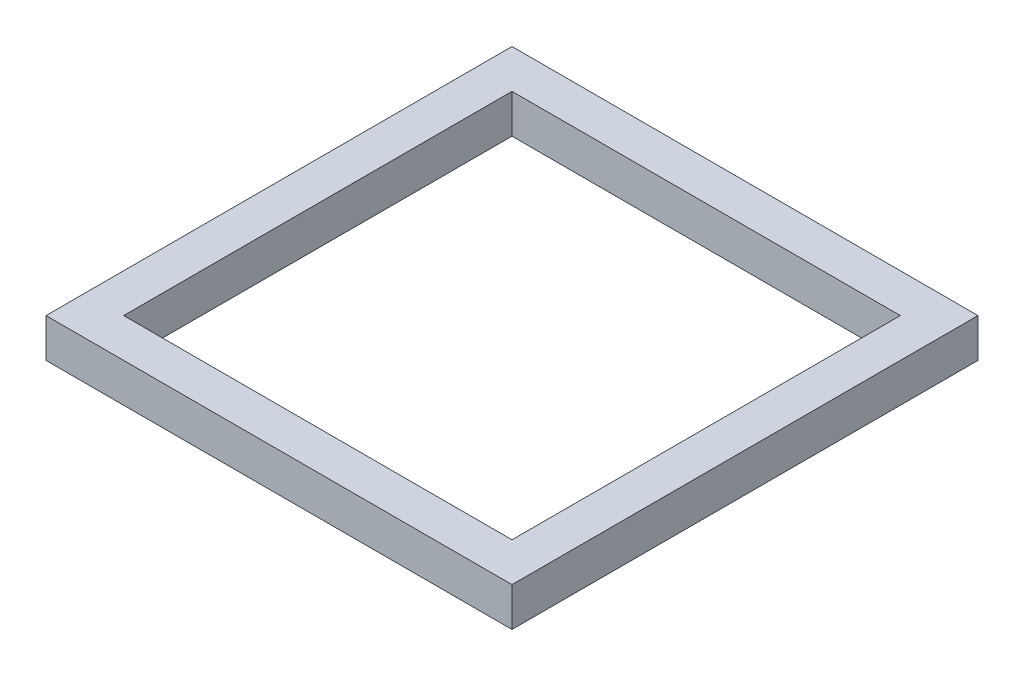
SolidWorks part; units mm, degrees
ref_plane "Front Plane" through (0, 0, 0) normal (0, 0, 1) x (1, 0, 0)
ref_plane "Top Plane" through (0, 0, 0) normal (0, 1, 0) x (1, 0, 0)
ref_plane "Right Plane" through (0, 0, 0) normal (1, 0, 0) x (0, 0, -1)
sketch "Sketch3" plane through (0, 0, 0) normal (0, 1, 0) x (1, 0, 0)
  line L0 (-25, 25) -> (25, 25)
  line L1 (-30, -30) -> (30, -30)
  line L2 (-30, -30) -> (-30, 30)
  line L3 (-30, 30) -> (30, 30)
  line L4 (30, -30) -> (30, 30)
  line L5 (-30, -30) -> (30, 30) construction
  line L6 (-30, 30) -> (30, -30) construction
  line L7 (25, -25) -> (25, 25)
  line L8 (-25, -25) -> (25, -25)
  line L9 (-25, -25) -> (-25, 25)
  point P0 (0, 0)
  dimension "D1" = 60
  dimension "D2" = 5
extrude "Boss-Extrude1" add sketch "Sketch3" along normal blind 5
